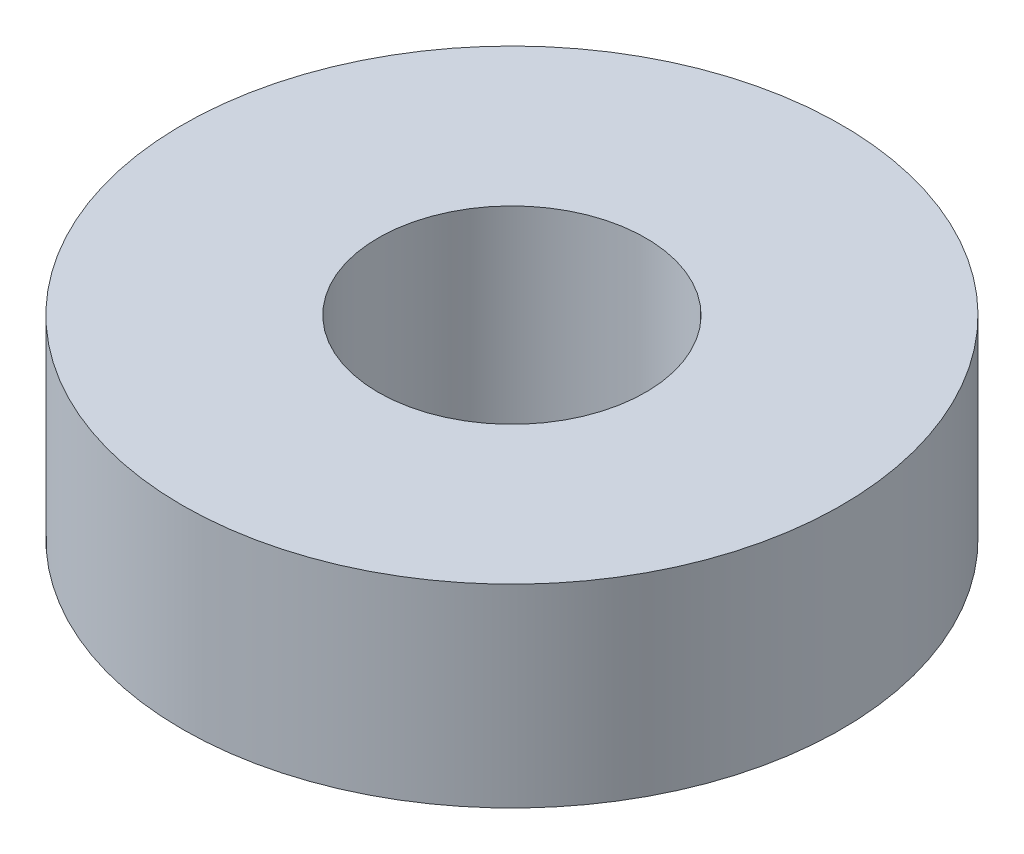
SolidWorks part; units mm, degrees
ref_plane "Plan de face" through (0, 0, 0) normal (0, 0, 1) x (1, 0, 0)
ref_plane "Plan de dessus" through (0, 0, 0) normal (0, 1, 0) x (1, 0, 0)
ref_plane "Plan de droite" through (0, 0, 0) normal (1, 0, 0) x (0, 0, -1)
sketch "Esquisse1" plane through (0, 0, 0) normal (0, 1, 0) x (1, 0, 0)
  circle A0 centre (0, 0) radius 3.45
  circle A1 centre (0, 0) radius 8.5
  dimension "D1" = 17
  dimension "D2" = 6.9
extrude "Boss.-Extru.1" add sketch "Esquisse1" along normal blind 5
